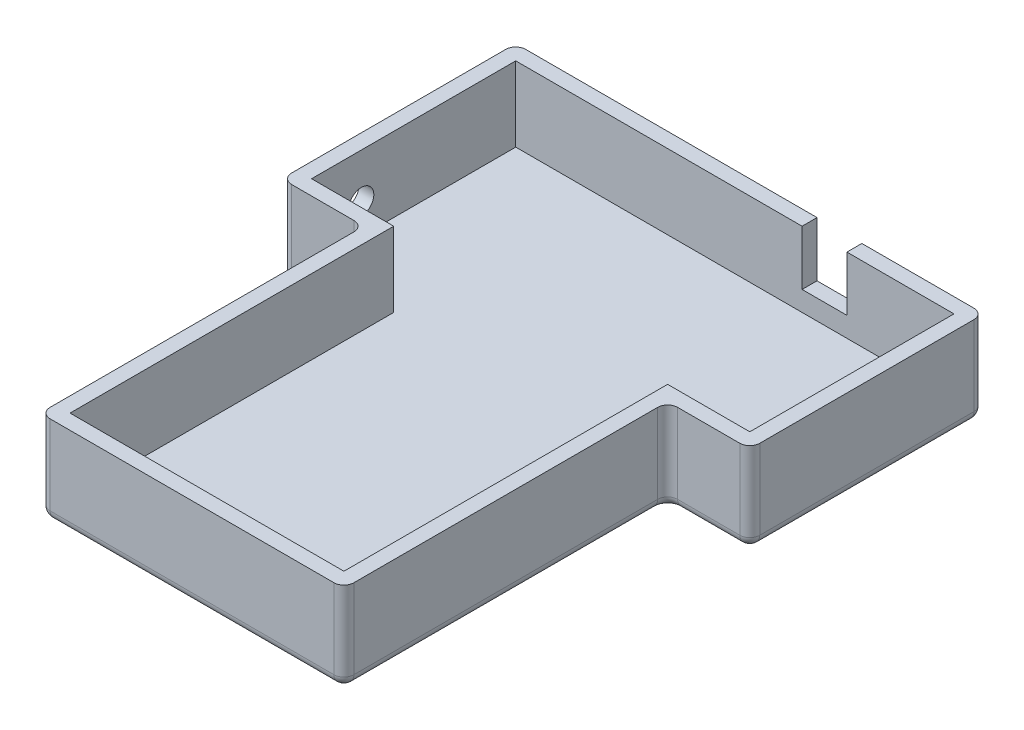
SolidWorks part; units mm, degrees
material "PEI"
ref_plane "Front Plane" through (0, 0, 0) normal (0, 0, 1) x (1, 0, 0)
ref_plane "Top Plane" through (0, 0, 0) normal (0, 1, 0) x (1, 0, 0)
ref_plane "Right Plane" through (0, 0, 0) normal (1, 0, 0) x (0, 0, -1)
sketch "Sketch1" plane through (0, 0, 0) normal (0, 1, 0) x (1, 0, 0)
  line L0 (0, 0) -> (88, 0)
  line L1 (88, 0) -> (88, -41)
  line L2 (88, -41) -> (71.5, -41)
  line L3 (71.5, -41) -> (71.5, -106)
  line L4 (71.5, -106) -> (16.5, -106)
  line L5 (16.5, -106) -> (16.5, -41)
  line L6 (16.5, -41) -> (0, -41)
  line L7 (0, -41) -> (0, 0)
  dimension "D1" = 88
  dimension "D2" = 55
  dimension "D3" = 41
  dimension "D4" = 65
extrude "Boss-Extrude1" add sketch "Sketch1" along normal blind 15
shell "Shell1" thickness 3
sketch "Sketch3" plane through (0, 0, -3) normal (0, 0, -1) x (-1, 0, 0)
  line L0 (-91, 6) -> (3, 6) construction
  line L1 (-91, 15) -> (-91, -3) construction
  line L2 (3, 15) -> (3, -3) construction
  line L3 (-44, 6) -> (-44, -3) construction
  line L4 (-91, -3) -> (3, -3) construction
  line L5 (-44, -3) -> (-44, 15) construction
  line L6 (-91, 15) -> (3, 15) construction
  line L8 (-66.5, 15) -> (-57.5, 15)
  line L9 (-66.5, 15) -> (-66.5, 4)
  line L10 (-66.5, 4) -> (-57.5, 4)
  line L11 (-57.5, 15) -> (-57.5, 4)
  line L12 (-66.5, 15) -> (-57.5, 4) construction
  line L13 (-66.5, 4) -> (-57.5, 15) construction
  point P13 (-62, 9.5)
  point P18 (-44, 1.5)
  dimension "D1" = 11
  dimension "D2" = 9
  dimension "D3" = 13.5
  dimension "D4" = 0
extrude "Cut-Extrude1" cut sketch "Sketch3" against normal blind 3
sketch "Sketch4" plane through (-3, 0, 0) normal (-1, 0, 0) x (0, 0, 1)
  line L0 (44, 15) -> (44, -3) construction
  line L1 (-3, 15) -> (44, 15) construction
  circle A0 centre (31, 6) radius 2.5
  dimension "D1" = 5
  dimension "D2" = 13
  dimension "D3" = 9
extrude "Cut-Extrude2" cut sketch "Sketch4" against normal blind 3
fillet "Fillet1" radius 2 16 edges at (5.25, -3, 44) (13.5, -3, 76.5) (44, -3, 109) (74.5, -3, 76.5) (82.75, -3, 44) (91, -3, 20.5) (44, -3, -3) (-3, -3, 20.5) (-3, 6, -3) (91, 6, -3) (91, 6, 44) (74.5, 6, 44) (74.5, 6, 109) (13.5, 6, 109) (13.5, 6, 44) (-3, 6, 44)
